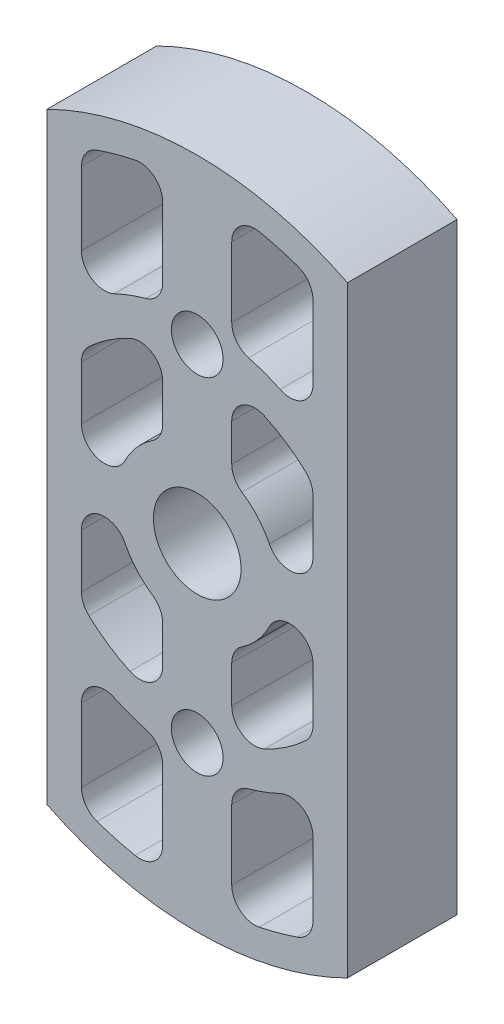
SolidWorks part; units mm, degrees
material "6061 Alloy"
ref_plane "Front Plane" through (0, 0, 0) normal (0, 0, 1) x (1, 0, 0)
ref_plane "Top Plane" through (0, 0, 0) normal (0, 1, 0) x (1, 0, 0)
ref_plane "Right Plane" through (0, 0, 0) normal (1, 0, 0) x (0, 0, -1)
sketch "Sketch1" plane through (0, 0, 0) normal (0, 0, 1) x (1, 0, 0)
  circle A0 centre (0, 0) radius 29.25
  dimension "D1" = 58.5
extrude "3/8" add sketch "Sketch1" along normal blind 9.525
sketch "Sketch2" plane through (0, 0, 9.525) normal (0, 0, 1) x (1, 0, 0)
  line L0 (0, 0) -> (0, 37.0794) construction
  line L1 (0, 0) -> (-34.7106, 0) construction
  line L2 (-3, 24.2193) -> (-3, 18.1547)
  line L3 (-10.0623, 23.3789) -> (-10.0623, 17.0174)
  line L4 (-3, 10.7221) -> (-3, 7.4833)
  line L5 (-10.0623, 8.6582) -> (-10.0623, 4)
  line L6 (3, 10.7221) -> (3, 7.4833)
  line L7 (10.0623, 8.6582) -> (10.0623, 4)
  line L8 (3, 24.2193) -> (3, 18.1547)
  line L9 (10.0623, 23.3789) -> (10.0623, 17.0174)
  line L10 (-3, -10.7221) -> (-3, -7.4833)
  line L11 (-10.0623, -8.6582) -> (-10.0623, -4)
  line L12 (3, -10.7221) -> (3, -7.4833)
  line L13 (10.0623, -8.6582) -> (10.0623, -4)
  line L14 (3, -24.2193) -> (3, -18.1547)
  line L15 (10.0623, -23.3789) -> (10.0623, -17.0174)
  line L16 (-3, -24.2193) -> (-3, -18.1547)
  line L17 (-10.0623, -23.3789) -> (-10.0623, -17.0174)
  arc A0 (-5.4044, 26.178) -> (-8.7143, 25.2696) centre (0, 0) ccw
  arc A1 (-4.469, 16.2265) -> (-7.206, 15.21) centre (0, 0) ccw
  circle A2 centre (0, 0) radius 29.25 construction
  arc A3 (-5.8453, 12.5347) -> (-9.4252, 10.1219) centre (0, 0) ccw
  arc A4 (-3.8889, 5.8204) -> (-6.2706, 3.1111) centre (0, 0) ccw
  arc A17 (-3, 7.4833) -> (-3.8889, 5.8204) centre (-5, 7.4833) cw
  arc A18 (-6.2706, 3.1111) -> (-10.0623, 4) centre (-8.0623, 4) cw
  arc A19 (-10.0623, 8.6582) -> (-9.4252, 10.1219) centre (-8.0623, 8.6582) cw
  arc A20 (-5.8453, 12.5347) -> (-3, 10.7221) centre (-5, 10.7221) cw
  arc A21 (-5.4044, 26.178) -> (-3, 24.2193) centre (-5, 24.2193) cw
  arc A22 (-8.7143, 25.2696) -> (-10.0623, 23.3789) centre (-8.0623, 23.3789) ccw
  arc A23 (-10.0623, 17.0174) -> (-7.206, 15.21) centre (-8.0623, 17.0174) ccw
  arc A24 (-4.469, 16.2265) -> (-3, 18.1547) centre (-5, 18.1547) ccw
  arc A25 (5.8453, 12.5347) -> (9.4252, 10.1219) centre (0, 0) cw
  arc A26 (5.8453, 12.5347) -> (3, 10.7221) centre (5, 10.7221) ccw
  arc A27 (3, 7.4833) -> (3.8889, 5.8204) centre (5, 7.4833) ccw
  arc A28 (3.8889, 5.8204) -> (6.2706, 3.1111) centre (0, 0) cw
  arc A29 (6.2706, 3.1111) -> (10.0623, 4) centre (8.0623, 4) ccw
  arc A30 (10.0623, 8.6582) -> (9.4252, 10.1219) centre (8.0623, 8.6582) ccw
  arc A31 (5.4044, 26.178) -> (8.7143, 25.2696) centre (0, 0) cw
  arc A32 (5.4044, 26.178) -> (3, 24.2193) centre (5, 24.2193) ccw
  arc A33 (4.469, 16.2265) -> (3, 18.1547) centre (5, 18.1547) cw
  arc A34 (4.469, 16.2265) -> (7.206, 15.21) centre (0, 0) cw
  arc A35 (8.7143, 25.2696) -> (10.0623, 23.3789) centre (8.0623, 23.3789) cw
  arc A36 (10.0623, 17.0174) -> (7.206, 15.21) centre (8.0623, 17.0174) cw
  arc A37 (-5.8453, -12.5347) -> (-9.4252, -10.1219) centre (0, 0) cw
  arc A38 (-5.8453, -12.5347) -> (-3, -10.7221) centre (-5, -10.7221) ccw
  arc A39 (-3, -7.4833) -> (-3.8889, -5.8204) centre (-5, -7.4833) ccw
  arc A40 (-3.8889, -5.8204) -> (-6.2706, -3.1111) centre (0, 0) cw
  arc A41 (-6.2706, -3.1111) -> (-10.0623, -4) centre (-8.0623, -4) ccw
  arc A42 (-10.0623, -8.6582) -> (-9.4252, -10.1219) centre (-8.0623, -8.6582) ccw
  arc A43 (5.8453, -12.5347) -> (3, -10.7221) centre (5, -10.7221) cw
  arc A44 (3, -7.4833) -> (3.8889, -5.8204) centre (5, -7.4833) cw
  arc A45 (3.8889, -5.8204) -> (6.2706, -3.1111) centre (0, 0) ccw
  arc A46 (6.2706, -3.1111) -> (10.0623, -4) centre (8.0623, -4) cw
  arc A47 (10.0623, -8.6582) -> (9.4252, -10.1219) centre (8.0623, -8.6582) cw
  arc A48 (5.8453, -12.5347) -> (9.4252, -10.1219) centre (0, 0) ccw
  arc A49 (5.4044, -26.178) -> (3, -24.2193) centre (5, -24.2193) cw
  arc A50 (4.469, -16.2265) -> (3, -18.1547) centre (5, -18.1547) ccw
  arc A51 (4.469, -16.2265) -> (7.206, -15.21) centre (0, 0) ccw
  arc A52 (10.0623, -17.0174) -> (7.206, -15.21) centre (8.0623, -17.0174) ccw
  arc A53 (8.7143, -25.2696) -> (10.0623, -23.3789) centre (8.0623, -23.3789) ccw
  arc A54 (5.4044, -26.178) -> (8.7143, -25.2696) centre (0, 0) ccw
  arc A55 (-5.4044, -26.178) -> (-8.7143, -25.2696) centre (0, 0) cw
  arc A56 (-5.4044, -26.178) -> (-3, -24.2193) centre (-5, -24.2193) ccw
  arc A57 (-4.469, -16.2265) -> (-3, -18.1547) centre (-5, -18.1547) cw
  arc A58 (-4.469, -16.2265) -> (-7.206, -15.21) centre (0, 0) cw
  arc A59 (-8.7143, -25.2696) -> (-10.0623, -23.3789) centre (-8.0623, -23.3789) cw
  arc A60 (-10.0623, -17.0174) -> (-7.206, -15.21) centre (-8.0623, -17.0174) cw
  point P24 (-3, 26.5611)
  point P31 (-3, 16.5611)
  point P32 (-24.268, 2.7579)
  point P33 (-17.7456, 8.8585)
  point P34 (-11.823, 5.3294)
  point P35 (-10.9161, 1.3557)
  point P41 (0, 0)
  point P107 (0, 0)
  dimension "D1" = 2.52
  dimension "D5" = 3
  dimension "D6" = 7
  dimension "D7" = 2
  dimension "D2" = 10
  dimension "D3" = 3
  dimension "D4" = 4
extrude "Cut-Extrude1" cut sketch "Sketch2" against normal up to surface (9.525 mm away) up to face at (29.25, 0, 0)
sketch "Sketch3" plane through (0, 0, 9.525) normal (0, 0, 1) x (1, 0, 0)
  line L0 (0, 15) -> (0, 0) construction
  circle A0 centre (0, 15) radius 2.25
  circle A1 centre (0, -15) radius 2.25
  point P12 (0, 0)
  dimension "D1" = 4.5
  dimension "D2" = 15
  dimension "D3" = 2
extrude "M4_through" cut sketch "Sketch3" against normal up to surface (9.525 mm away) up to face at (-6.4532, -7.7476, 0)
sketch "Sketch4" plane through (0, 0, 9.525) normal (0, 0, 1) x (1, 0, 0)
  circle A0 centre (0, 0) radius 3.81
  dimension "D1" = 7.62
extrude "3/8_DRILL" cut sketch "Sketch4" against normal up to surface (9.525 mm away) up to face at (2.25, 15, 0)
sketch "Sketch6" plane through (0, 0, 9.525) normal (0, 0, 1) x (1, 0, 0)
  line L0 (-10.0623, 23.3789) -> (-10.0623, 17.0174) construction
  line L1 (-31.0916, 27.4538) -> (-13.0623, 27.4538)
  line L2 (-31.0916, 27.4538) -> (-31.0916, -30.1261)
  line L3 (-31.0916, -30.1261) -> (-13.0623, -30.1261)
  line L4 (-13.0623, 27.4538) -> (-13.0623, -30.1261)
  line L5 (-22.0769, -30.1261) -> (-22.0769, 27.4538) construction
  line L6 (-31.0916, -1.3362) -> (-13.0623, -1.3362) construction
  line L7 (0, 0) -> (0, 9.1394) construction
  line L8 (31.0916, -30.1261) -> (13.0623, -30.1261)
  line L9 (13.0623, 27.4538) -> (13.0623, -30.1261)
  line L10 (31.0916, 27.4538) -> (13.0623, 27.4538)
  line L11 (31.0916, 27.4538) -> (31.0916, -30.1261)
  point P432 (-22.0769, -1.3362)
  dimension "D1" = 3
extrude "Cut-Extrude2" cut sketch "Sketch6" against normal up to surface (9.525 mm away) up to face at (3.81, 0, 0)
